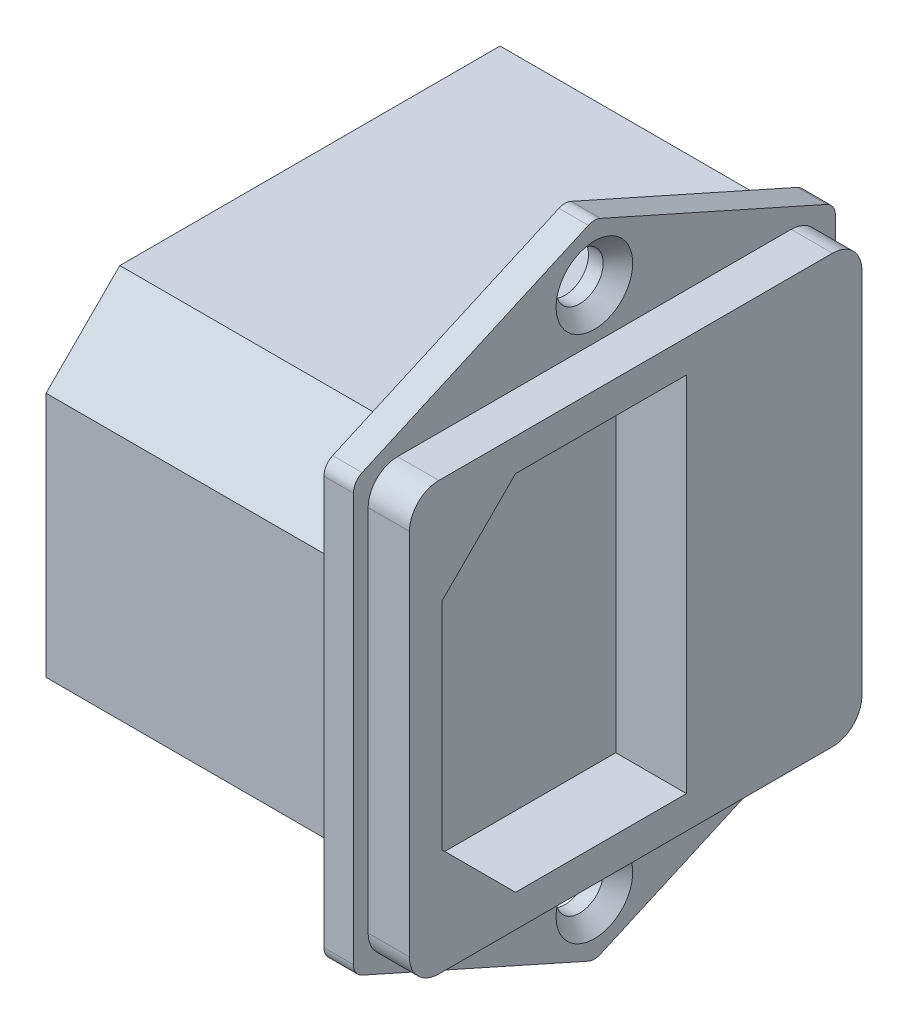
SolidWorks part; units mm, degrees
ref_plane "Front Plane" through (0, 0, 0) normal (1, 0, 0) x (0, 1, 0)
ref_plane "Top Plane" through (0, 0, 0) normal (0, 0, 1) x (0, 1, 0)
ref_plane "Right Plane" through (0, 0, 0) normal (0, 1, 0) x (-1, 0, 0)
sketch "Sketch1" plane through (0, 0, 0) normal (1, 0, 0) x (0, 1, 0)
  line L0 (-14.5, 16.35) -> (-21.8, 0)
  line L1 (-14.5, -16.35) -> (14.5, -16.35)
  line L2 (-14.5, -16.35) -> (-14.5, 16.35)
  line L3 (-14.5, 16.35) -> (14.5, 16.35)
  line L4 (14.5, -16.35) -> (14.5, 16.35)
  line L5 (-14.5, -16.35) -> (14.5, 16.35) construction
  line L6 (-14.5, 16.35) -> (14.5, -16.35) construction
  line L7 (-21.8, 0) -> (-14.5, -16.35)
  line L8 (14.5, -16.35) -> (21.8, 0)
  line L9 (21.8, 0) -> (14.5, 16.35)
  line L10 (-14.5, 16.35) -> (-14.5, -16.35)
  line L11 (14.5, 16.35) -> (14.5, -16.35)
  line L12 (17.9, 0) -> (-17.9, 0) construction
  circle A0 centre (-17.9, 0) radius 1.6
  circle A1 centre (17.9, 0) radius 1.6
  point P0 (0, 0)
  point P11 (0, 0)
  dimension "D4" = 3.2
  dimension "D1" = 43.6
  dimension "D2" = 32.7
  dimension "D3" = 29
  dimension "D5" = 35.8
extrude "Boss-Extrude1" add sketch "Sketch1" along normal blind 2 contours L8 L9 L4 A1 | L1 L4 L3 L2 | L0 L7 L2 A0
sketch "Sketch2" plane through (2, 0, 0) normal (1, 0, 0) x (0, 1, 0)
  line L1 (14.5, -15.35) -> (-14.5, -15.35)
  line L2 (14.5, -15.35) -> (14.5, 15.35)
  line L3 (14.5, 15.35) -> (-14.5, 15.35)
  line L4 (-14.5, -15.35) -> (-14.5, 15.35)
  line L5 (14.5, -15.35) -> (-14.5, 15.35) construction
  line L6 (14.5, 15.35) -> (-14.5, -15.35) construction
  point P0 (0, 0)
  dimension "D1" = 30.7
  dimension "D2" = 29
extrude "Boss-Extrude2" add sketch "Sketch2" along normal blind 2.8
sketch "Sketch3" plane through (4.8, 0, 0) normal (1, 0, 0) x (0, 1, 0)
  line L0 (0, 0) -> (0, 4.85) construction
  line L2 (-12.3, 13.15) -> (12.3, 13.15)
  line L3 (-12.3, 13.15) -> (-12.3, -3.45)
  line L4 (-12.3, -3.45) -> (12.3, -3.45)
  line L5 (12.3, 13.15) -> (12.3, -3.45)
  line L6 (-12.3, 13.15) -> (12.3, -3.45) construction
  line L7 (-12.3, -3.45) -> (12.3, 13.15) construction
  line L8 (-12.3, 13.15) -> (-14.5, 15.35) construction
  line L9 (14.5, 15.35) -> (-14.5, 15.35) construction
  dimension "D1" = 24.6
  dimension "D2" = 16.6
  dimension "D3" = 45
extrude "Cut-Extrude1" cut sketch "Sketch3" against normal through all
chamfer "Chamfer1" distance 1 angle 45 2 edges at (2, 17.9, -1.6) (2, -17.9, -1.6)
chamfer "Chamfer2" distance 5 angle 45 2 edges at (2.4, 12.3, 13.15) (2.4, -12.3, 13.15)
sketch "Sketch4" plane through (0, 0, 0) normal (-1, 0, 0) x (0, -1, 0)
  line L0 (0, 0) -> (0, 15.4) construction
  line L1 (0, 0) -> (0, -15.4) construction
  line L2 (-8.35, 15.4) -> (-8.35, -15.4) construction
  line L3 (0, 0) -> (-8.35, 0) construction
  line L6 (-13.35, 10.4) -> (-13.35, -15.4)
  line L7 (-13.35, -15.4) -> (13.35, -15.4)
  line L8 (13.35, -15.4) -> (13.35, 10.4)
  line L12 (8.35, 15.4) -> (13.35, 10.4)
  line L13 (-13.35, 10.4) -> (-8.35, 15.4)
  line L14 (-8.35, 15.4) -> (8.35, 15.4)
  point P2 (-7.2079, 15.4)
  dimension "D2" = 26.7
  dimension "D1" = 30.8
  dimension "D3" = 5
extrude "Boss-Extrude3" add sketch "Sketch4" along normal blind 19.8
fillet "Fillet1" radius 1 6 edges at (1, -21.8, 0) (1, -14.5, -16.35) (1, 14.5, -16.35) (1, 21.8, 0) (1, 14.5, 16.35) (1, -14.5, 16.35)
fillet "Fillet2" radius 2 4 edges at (3.4, -14.5, 15.35) (3.4, 14.5, 15.35) (3.4, 14.5, -15.35) (3.4, -14.5, -15.35)
